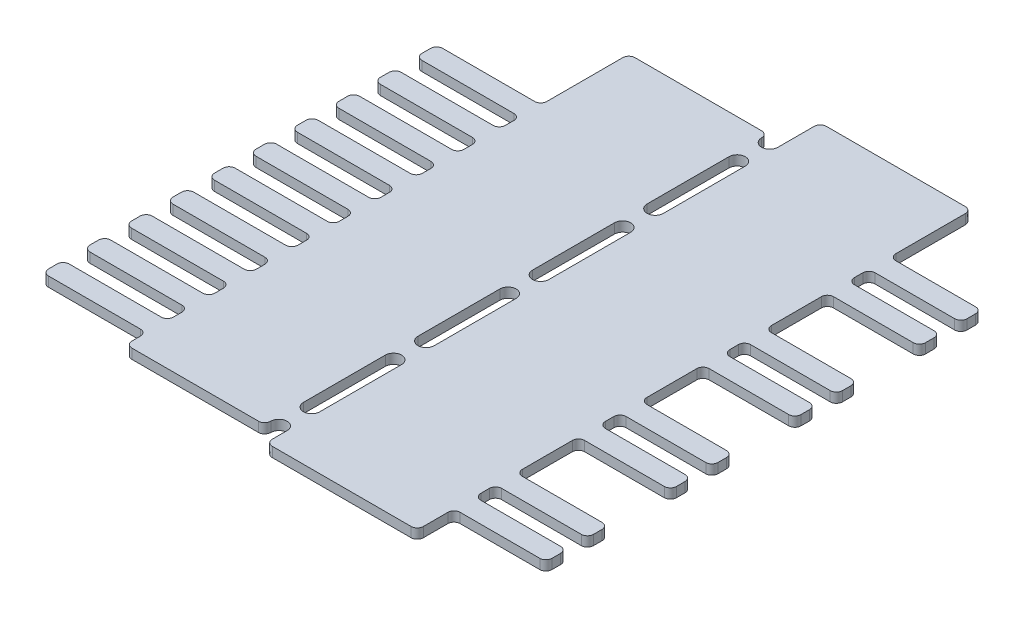
SolidWorks part; units mm, degrees
ref_plane "Front Plane" through (0, 0, 0) normal (0, 0, 1) x (1, 0, 0)
ref_plane "Top Plane" through (0, 0, 0) normal (0, 1, 0) x (1, 0, 0)
ref_plane "Right Plane" through (0, 0, 0) normal (1, 0, 0) x (0, 0, -1)
sketch "Sketch1" plane through (0, 0, 0) normal (0, 1, 0) x (1, 0, 0)
  line L0 (-0.75, 10) -> (-10.5, 10)
  line L2 (0, 9.25) -> (0, 0.75)
  line L5 (-11.25, 11.27) -> (0, 11.27) construction
  line L7 (-11.25, 10.75) -> (-11.25, 11.79)
  line L8 (-10.5, 12.54) -> (-0.75, 12.54)
  line L12 (0, 14.33) -> (0, 13.29)
  line L17 (-0.75, 15.08) -> (-10.5, 15.08)
  line L22 (-11.25, 15.83) -> (-11.25, 16.87)
  line L27 (-10.5, 17.62) -> (-0.75, 17.62)
  line L56 (17.75, 0) -> (0.75, 0)
  line L84 (0, 19.41) -> (0, 10.91) [skipped]
  line L85 (-0.75, 20.16) -> (-10.5, 20.16) [skipped]
  line L86 (-11.25, 20.91) -> (-11.25, 21.95) [skipped]
  line L87 (-10.5, 22.7) -> (-0.75, 22.7) [skipped]
  line L88 (0, 24.49) -> (0, 15.99) [skipped]
  line L89 (-0.75, 25.24) -> (-10.5, 25.24) [skipped]
  line L90 (-11.25, 25.99) -> (-11.25, 27.03) [skipped]
  line L91 (-10.5, 27.78) -> (-0.75, 27.78) [skipped]
  line L92 (0, 29.57) -> (0, 21.07) [skipped]
  line L93 (-0.75, 30.32) -> (-10.5, 30.32) [skipped]
  line L94 (-11.25, 31.07) -> (-11.25, 32.11) [skipped]
  line L95 (-10.5, 32.86) -> (-0.75, 32.86) [skipped]
  line L96 (0, 34.65) -> (0, 26.15) [skipped]
  line L97 (-0.75, 35.4) -> (-10.5, 35.4) [skipped]
  line L98 (-11.25, 36.15) -> (-11.25, 37.19) [skipped]
  line L99 (-10.5, 37.94) -> (-0.75, 37.94) [skipped]
  line L100 (0, 39.73) -> (0, 31.23) [skipped]
  line L101 (-0.75, 40.48) -> (-10.5, 40.48) [skipped]
  line L102 (-11.25, 41.23) -> (-11.25, 42.27) [skipped]
  line L103 (-10.5, 43.02) -> (-0.75, 43.02) [skipped]
  line L104 (0, 44.81) -> (0, 36.31) [skipped]
  line L105 (-0.75, 45.56) -> (-10.5, 45.56) [skipped]
  line L106 (-11.25, 46.31) -> (-11.25, 47.35) [skipped]
  line L107 (-10.5, 48.1) -> (-0.75, 48.1) [skipped]
  line L108 (0, 49.89) -> (0, 41.39) [skipped]
  line L109 (-0.75, 50.64) -> (-10.5, 50.64) [skipped]
  line L110 (-11.25, 51.39) -> (-11.25, 52.43) [skipped]
  line L111 (-10.5, 53.18) -> (-0.75, 53.18) [skipped]
  line L112 (0, 54.97) -> (0, 46.47) [skipped]
  line L113 (-0.75, 55.72) -> (-10.5, 55.72) [skipped]
  line L114 (-11.25, 56.47) -> (-11.25, 57.51) [skipped]
  line L115 (-10.5, 58.26) -> (-0.75, 58.26) [skipped]
  line L116 (-0.75, 25.24) -> (-10.5, 25.24)
  line L117 (-11.25, 25.99) -> (-11.25, 27.03)
  line L118 (-10.5, 27.78) -> (-0.75, 27.78)
  line L119 (0, 29.57) -> (0, 28.53)
  line L120 (-0.75, 30.32) -> (-10.5, 30.32)
  line L121 (-11.25, 31.07) -> (-11.25, 32.11)
  line L122 (-10.5, 32.86) -> (-0.75, 32.86)
  line L123 (-0.75, 40.48) -> (-10.5, 40.48)
  line L124 (-11.25, 41.23) -> (-11.25, 42.27)
  line L125 (-10.5, 43.02) -> (-0.75, 43.02)
  line L126 (0, 44.81) -> (0, 43.77)
  line L127 (-0.75, 45.56) -> (-10.5, 45.56)
  line L128 (-11.25, 46.31) -> (-11.25, 47.35)
  line L129 (-10.5, 48.1) -> (-0.75, 48.1)
  line L130 (-0.75, 55.72) -> (-10.5, 55.72)
  line L131 (-11.25, 56.47) -> (-11.25, 57.51)
  line L132 (-10.5, 58.26) -> (-0.75, 58.26)
  line L133 (0, 60.05) -> (0, 59.01)
  line L134 (-0.75, 60.8) -> (-10.5, 60.8)
  line L135 (-11.25, 61.55) -> (-11.25, 62.59)
  line L136 (-10.5, 63.34) -> (-0.75, 63.34)
  line L137 (0, 24.49) -> (0, 18.37)
  line L138 (0, 33.61) -> (0, 39.73)
  line L139 (0, 48.85) -> (0, 54.97)
  line L140 (0, 64.09) -> (0, 67.09)
  line L141 (0.75, 67.84) -> (17.75, 67.84)
  line L145 (38.25, 15.2205) -> (49.5, 15.2205)
  line L157 (37.5, 14.4705) -> (37.5, 5.183)
  line L158 (36.75, 4.433) -> (21.25, 4.433)
  line L160 (21.25, 66.0205) -> (36.75, 66.0205)
  line L188 (19.5, 5.183) -> (19.5, 54.2098) construction
  line L190 (18.5, 0.75) -> (18.5, 5.183)
  line L191 (20.5, 5.183) -> (19.5, 5.183) construction
  line L192 (20.5, 65.2705) -> (19.5, 65.2705) construction
  line L193 (20, 54.7098) -> (20, 58.84) construction
  line L194 (19, 58.84) -> (19, 54.7098) construction
  line L195 (18.5, 65.2705) -> (18.5, 67.09)
  line L196 (19.5, 54.2098) -> (19.5, 55.2098) construction
  line L197 (19.5, 55.2098) -> (19.5, 58.34) construction
  line L198 (19.5, 58.34) -> (19.5, 59.34) construction
  line L199 (19.5, 59.34) -> (19.5, 65.2705) construction
  line L200 (50.25, 15.9705) -> (50.25, 17.0105)
  line L201 (49.5, 17.7605) -> (38.25, 17.7605)
  line L202 (37.5, 18.5105) -> (37.5, 19.5505)
  line L204 (50.25, 21.0505) -> (50.25, 22.0905)
  line L205 (49.5, 22.8405) -> (38.25, 22.8405)
  line L206 (37.5, 23.5905) -> (37.5, 24.6305)
  line L207 (38.25, 20.3005) -> (49.5, 20.3005)
  line L208 (50.25, 26.1305) -> (50.25, 27.1705)
  line L209 (49.5, 27.9205) -> (38.25, 27.9205)
  line L210 (37.5, 28.6705) -> (37.5, 29.7105)
  line L212 (19.5, 65.2705) -> (18.5, 65.2705) construction
  line L213 (19.5, 65.2705) -> (19.5, 59.9038) construction
  line L214 (38.25, 25.3805) -> (49.5, 25.3805)
  line L215 (50.25, 31.2105) -> (50.25, 32.2505)
  line L216 (49.5, 33.0005) -> (38.25, 33.0005)
  line L217 (37.5, 33.7505) -> (37.5, 34.7905)
  line L218 (19.5, 5.183) -> (18.5, 5.183) construction
  line L219 (38.25, 30.4605) -> (49.5, 30.4605)
  line L220 (50.25, 36.2905) -> (50.25, 37.3305)
  line L221 (49.5, 38.0805) -> (38.25, 38.0805)
  line L222 (37.5, 38.8305) -> (37.5, 39.8705)
  line L223 (38.25, 35.5405) -> (49.5, 35.5405)
  line L224 (50.25, 41.3705) -> (50.25, 42.4105)
  line L225 (49.5, 43.1605) -> (38.25, 43.1605)
  line L226 (37.5, 43.9105) -> (37.5, 44.9505)
  line L227 (38.25, 40.6205) -> (49.5, 40.6205)
  line L228 (50.25, 46.4505) -> (50.25, 47.4905)
  line L229 (49.5, 48.2405) -> (38.25, 48.2405)
  line L230 (37.5, 48.9905) -> (37.5, 50.0305)
  line L231 (38.25, 45.7005) -> (49.5, 45.7005)
  line L232 (50.25, 51.5305) -> (50.25, 52.5705)
  line L233 (49.5, 53.3205) -> (38.25, 53.3205)
  line L234 (37.5, 54.0705) -> (37.5, 55.1105)
  line L235 (38.25, 50.7805) -> (49.5, 50.7805)
  line L236 (50.25, 56.6105) -> (50.25, 57.6505)
  line L237 (49.5, 58.4005) -> (38.25, 58.4005)
  line L238 (37.5, 59.1505) -> (37.5, 60.1905)
  line L239 (38.25, 55.8605) -> (49.5, 55.8605)
  line L240 (50.25, 61.6905) -> (50.25, 62.7305)
  line L241 (49.5, 63.4805) -> (38.25, 63.4805)
  line L242 (37.5, 64.2305) -> (37.5, 65.2705)
  line L243 (38.25, 60.9405) -> (49.5, 60.9405)
  arc A0 (-0.75, 12.54) -> (0, 13.29) centre (-0.75, 13.29) ccw
  arc A1 (-11.25, 11.79) -> (-10.5, 12.54) centre (-10.5, 11.79) cw
  arc A2 (-10.5, 10) -> (-11.25, 10.75) centre (-10.5, 10.75) cw
  arc A3 (0, 0.75) -> (0.75, 0) centre (0.75, 0.75) ccw
  arc A4 (-0.75, 10) -> (0, 9.25) centre (-0.75, 9.25) cw
  arc A5 (18.5, 0.75) -> (17.75, 0) centre (17.75, 0.75) cw
  arc A6 (-0.75, 15.08) -> (0, 14.33) centre (-0.75, 14.33) cw
  arc A7 (-10.5, 15.08) -> (-11.25, 15.83) centre (-10.5, 15.83) cw
  arc A8 (-11.25, 16.87) -> (-10.5, 17.62) centre (-10.5, 16.87) cw
  arc A9 (-0.75, 17.62) -> (0, 18.37) centre (-0.75, 18.37) ccw
  arc A44 (-0.75, 20.16) -> (0, 19.41) centre (-0.75, 19.41) cw [skipped]
  arc A45 (-10.5, 20.16) -> (-11.25, 20.91) centre (-10.5, 20.91) cw [skipped]
  arc A46 (-11.25, 21.95) -> (-10.5, 22.7) centre (-10.5, 21.95) cw [skipped]
  arc A47 (-0.75, 22.7) -> (0, 23.45) centre (-0.75, 23.45) ccw [skipped]
  arc A48 (-0.75, 25.24) -> (0, 24.49) centre (-0.75, 24.49) cw [skipped]
  arc A49 (-10.5, 25.24) -> (-11.25, 25.99) centre (-10.5, 25.99) cw [skipped]
  arc A50 (-11.25, 27.03) -> (-10.5, 27.78) centre (-10.5, 27.03) cw [skipped]
  arc A51 (-0.75, 27.78) -> (0, 28.53) centre (-0.75, 28.53) ccw [skipped]
  arc A52 (-0.75, 30.32) -> (0, 29.57) centre (-0.75, 29.57) cw [skipped]
  arc A53 (-10.5, 30.32) -> (-11.25, 31.07) centre (-10.5, 31.07) cw [skipped]
  arc A54 (-11.25, 32.11) -> (-10.5, 32.86) centre (-10.5, 32.11) cw [skipped]
  arc A55 (-0.75, 32.86) -> (0, 33.61) centre (-0.75, 33.61) ccw [skipped]
  arc A56 (-0.75, 35.4) -> (0, 34.65) centre (-0.75, 34.65) cw [skipped]
  arc A57 (-10.5, 35.4) -> (-11.25, 36.15) centre (-10.5, 36.15) cw [skipped]
  arc A58 (-11.25, 37.19) -> (-10.5, 37.94) centre (-10.5, 37.19) cw [skipped]
  arc A59 (-0.75, 37.94) -> (0, 38.69) centre (-0.75, 38.69) ccw [skipped]
  arc A60 (-0.75, 40.48) -> (0, 39.73) centre (-0.75, 39.73) cw [skipped]
  arc A61 (-10.5, 40.48) -> (-11.25, 41.23) centre (-10.5, 41.23) cw [skipped]
  arc A62 (-11.25, 42.27) -> (-10.5, 43.02) centre (-10.5, 42.27) cw [skipped]
  arc A63 (-0.75, 43.02) -> (0, 43.77) centre (-0.75, 43.77) ccw [skipped]
  arc A64 (-0.75, 45.56) -> (0, 44.81) centre (-0.75, 44.81) cw [skipped]
  arc A65 (-10.5, 45.56) -> (-11.25, 46.31) centre (-10.5, 46.31) cw [skipped]
  arc A66 (-11.25, 47.35) -> (-10.5, 48.1) centre (-10.5, 47.35) cw [skipped]
  arc A67 (-0.75, 48.1) -> (0, 48.85) centre (-0.75, 48.85) ccw [skipped]
  arc A68 (-0.75, 50.64) -> (0, 49.89) centre (-0.75, 49.89) cw [skipped]
  arc A69 (-10.5, 50.64) -> (-11.25, 51.39) centre (-10.5, 51.39) cw [skipped]
  arc A70 (-11.25, 52.43) -> (-10.5, 53.18) centre (-10.5, 52.43) cw [skipped]
  arc A71 (-0.75, 53.18) -> (0, 53.93) centre (-0.75, 53.93) ccw [skipped]
  arc A72 (-0.75, 55.72) -> (0, 54.97) centre (-0.75, 54.97) cw [skipped]
  arc A73 (-10.5, 55.72) -> (-11.25, 56.47) centre (-10.5, 56.47) cw [skipped]
  arc A74 (-11.25, 57.51) -> (-10.5, 58.26) centre (-10.5, 57.51) cw [skipped]
  arc A75 (-0.75, 58.26) -> (0, 59.01) centre (-0.75, 59.01) ccw [skipped]
  arc A76 (-0.75, 27.78) -> (0, 28.53) centre (-0.75, 28.53) ccw
  arc A77 (-11.25, 27.03) -> (-10.5, 27.78) centre (-10.5, 27.03) cw
  arc A78 (-10.5, 25.24) -> (-11.25, 25.99) centre (-10.5, 25.99) cw
  arc A79 (-0.75, 25.24) -> (0, 24.49) centre (-0.75, 24.49) cw
  arc A80 (-0.75, 30.32) -> (0, 29.57) centre (-0.75, 29.57) cw
  arc A81 (-10.5, 30.32) -> (-11.25, 31.07) centre (-10.5, 31.07) cw
  arc A82 (-11.25, 32.11) -> (-10.5, 32.86) centre (-10.5, 32.11) cw
  arc A83 (-0.75, 32.86) -> (0, 33.61) centre (-0.75, 33.61) ccw
  arc A84 (-0.75, 43.02) -> (0, 43.77) centre (-0.75, 43.77) ccw
  arc A85 (-11.25, 42.27) -> (-10.5, 43.02) centre (-10.5, 42.27) cw
  arc A86 (-10.5, 40.48) -> (-11.25, 41.23) centre (-10.5, 41.23) cw
  arc A87 (-0.75, 40.48) -> (0, 39.73) centre (-0.75, 39.73) cw
  arc A88 (-0.75, 45.56) -> (0, 44.81) centre (-0.75, 44.81) cw
  arc A89 (-10.5, 45.56) -> (-11.25, 46.31) centre (-10.5, 46.31) cw
  arc A90 (-11.25, 47.35) -> (-10.5, 48.1) centre (-10.5, 47.35) cw
  arc A91 (-0.75, 48.1) -> (0, 48.85) centre (-0.75, 48.85) ccw
  arc A92 (-0.75, 58.26) -> (0, 59.01) centre (-0.75, 59.01) ccw
  arc A93 (-11.25, 57.51) -> (-10.5, 58.26) centre (-10.5, 57.51) cw
  arc A94 (-10.5, 55.72) -> (-11.25, 56.47) centre (-10.5, 56.47) cw
  arc A95 (-0.75, 55.72) -> (0, 54.97) centre (-0.75, 54.97) cw
  arc A96 (-0.75, 60.8) -> (0, 60.05) centre (-0.75, 60.05) cw
  arc A97 (-10.5, 60.8) -> (-11.25, 61.55) centre (-10.5, 61.55) cw
  arc A98 (-11.25, 62.59) -> (-10.5, 63.34) centre (-10.5, 62.59) cw
  arc A99 (-0.75, 63.34) -> (0, 64.09) centre (-0.75, 64.09) ccw
  arc A100 (0, 67.09) -> (0.75, 67.84) centre (0.75, 67.09) cw
  arc A101 (17.75, 67.84) -> (18.5, 67.09) centre (17.75, 67.09) cw
  arc A107 (20.5, 65.2705) -> (21.25, 66.0205) centre (21.25, 65.2705) cw
  arc A144 (37.5, 5.183) -> (36.75, 4.433) centre (36.75, 5.183) cw
  arc A145 (21.25, 4.433) -> (20.5, 5.183) centre (21.25, 5.183) cw
  arc A147 (20.5, 5.183) -> (18.5, 5.183) centre (19.5, 5.183) ccw
  arc A148 (18.5, 5.183) -> (20.5, 5.183) centre (19.5, 5.183) ccw construction
  arc A149 (20, 58.84) -> (19, 58.84) centre (19.5, 58.84) ccw construction
  arc A150 (19, 54.7098) -> (20, 54.7098) centre (19.5, 54.7098) ccw construction
  arc A151 (19.5, 55.2098) -> (19, 54.7098) centre (19.5, 54.7098) ccw construction
  arc A152 (20, 54.7098) -> (19.5, 55.2098) centre (19.5, 54.7098) ccw construction
  arc A153 (19.5, 58.34) -> (20, 58.84) centre (19.5, 58.84) ccw construction
  arc A154 (19, 58.84) -> (19.5, 58.34) centre (19.5, 58.84) ccw construction
  arc A155 (18.5, 65.2705) -> (20.5, 65.2705) centre (19.5, 65.2705) ccw
  arc A156 (20.5, 65.2705) -> (18.5, 65.2705) centre (19.5, 65.2705) ccw construction
  arc A157 (38.25, 17.7605) -> (37.5, 18.5105) centre (38.25, 18.5105) cw
  arc A158 (50.25, 17.0105) -> (49.5, 17.7605) centre (49.5, 17.0105) ccw
  arc A159 (49.5, 15.2205) -> (50.25, 15.9705) centre (49.5, 15.9705) ccw
  arc A160 (37.5, 14.4705) -> (38.25, 15.2205) centre (38.25, 14.4705) cw
  arc A161 (38.25, 22.8405) -> (37.5, 23.5905) centre (38.25, 23.5905) cw
  arc A162 (50.25, 22.0905) -> (49.5, 22.8405) centre (49.5, 22.0905) ccw
  arc A163 (49.5, 20.3005) -> (50.25, 21.0505) centre (49.5, 21.0505) ccw
  arc A164 (37.5, 19.5505) -> (38.25, 20.3005) centre (38.25, 19.5505) cw
  arc A165 (38.25, 27.9205) -> (37.5, 28.6705) centre (38.25, 28.6705) cw
  arc A166 (50.25, 27.1705) -> (49.5, 27.9205) centre (49.5, 27.1705) ccw
  arc A167 (49.5, 25.3805) -> (50.25, 26.1305) centre (49.5, 26.1305) ccw
  arc A168 (37.5, 24.6305) -> (38.25, 25.3805) centre (38.25, 24.6305) cw
  arc A169 (38.25, 33.0005) -> (37.5, 33.7505) centre (38.25, 33.7505) cw
  arc A170 (50.25, 32.2505) -> (49.5, 33.0005) centre (49.5, 32.2505) ccw
  arc A171 (49.5, 30.4605) -> (50.25, 31.2105) centre (49.5, 31.2105) ccw
  arc A172 (37.5, 29.7105) -> (38.25, 30.4605) centre (38.25, 29.7105) cw
  arc A173 (38.25, 38.0805) -> (37.5, 38.8305) centre (38.25, 38.8305) cw
  arc A174 (50.25, 37.3305) -> (49.5, 38.0805) centre (49.5, 37.3305) ccw
  arc A175 (49.5, 35.5405) -> (50.25, 36.2905) centre (49.5, 36.2905) ccw
  arc A176 (37.5, 34.7905) -> (38.25, 35.5405) centre (38.25, 34.7905) cw
  arc A177 (38.25, 43.1605) -> (37.5, 43.9105) centre (38.25, 43.9105) cw
  arc A178 (50.25, 42.4105) -> (49.5, 43.1605) centre (49.5, 42.4105) ccw
  arc A179 (49.5, 40.6205) -> (50.25, 41.3705) centre (49.5, 41.3705) ccw
  arc A180 (37.5, 39.8705) -> (38.25, 40.6205) centre (38.25, 39.8705) cw
  arc A181 (38.25, 48.2405) -> (37.5, 48.9905) centre (38.25, 48.9905) cw
  arc A182 (50.25, 47.4905) -> (49.5, 48.2405) centre (49.5, 47.4905) ccw
  arc A183 (49.5, 45.7005) -> (50.25, 46.4505) centre (49.5, 46.4505) ccw
  arc A184 (37.5, 44.9505) -> (38.25, 45.7005) centre (38.25, 44.9505) cw
  arc A185 (38.25, 53.3205) -> (37.5, 54.0705) centre (38.25, 54.0705) cw
  arc A186 (50.25, 52.5705) -> (49.5, 53.3205) centre (49.5, 52.5705) ccw
  arc A187 (49.5, 50.7805) -> (50.25, 51.5305) centre (49.5, 51.5305) ccw
  arc A188 (37.5, 50.0305) -> (38.25, 50.7805) centre (38.25, 50.0305) cw
  arc A189 (38.25, 58.4005) -> (37.5, 59.1505) centre (38.25, 59.1505) cw
  arc A190 (50.25, 57.6505) -> (49.5, 58.4005) centre (49.5, 57.6505) ccw
  arc A191 (49.5, 55.8605) -> (50.25, 56.6105) centre (49.5, 56.6105) ccw
  arc A192 (37.5, 55.1105) -> (38.25, 55.8605) centre (38.25, 55.1105) cw
  arc A193 (38.25, 63.4805) -> (37.5, 64.2305) centre (38.25, 64.2305) cw
  arc A194 (50.25, 62.7305) -> (49.5, 63.4805) centre (49.5, 62.7305) ccw
  arc A195 (49.5, 60.9405) -> (50.25, 61.6905) centre (49.5, 61.6905) ccw
  arc A196 (37.5, 60.1905) -> (38.25, 60.9405) centre (38.25, 60.1905) cw
  arc A197 (37.5, 65.2705) -> (36.75, 66.0205) centre (36.75, 65.2705) ccw
  point P0 (0, 0)
  point P48 (-11.25, 12.54)
  point P69 (-11.25, 10)
  point P78 (0, 0)
  point P81 (0, 10)
  point P132 (29, 4.433)
  point P390 (43.875, 15.2205)
  dimension "D6" = 0.75
  dimension "D7" = 0.75
  dimension "D8" = 4
  dimension "D9" = 10.16
  dimension "D11" = 0.75
  dimension "D13" = 4.433
  dimension "D14" = 0.75
  dimension "D15" = 9
  dimension "D16" = 0.75
  dimension "D12" = 4.5
  dimension "D21" = 0.75
  dimension "D22" = 18.5
  dimension "D5" = 2
  dimension "D24" = 4.1302
  dimension "D25" = 17
  dimension "D17" = 0.75
  dimension "D1" = 2.54
  dimension "D2" = 10.5
  dimension "D3" = 10
  dimension "D4" = 10
  dimension "D10" = 5.08
  dimension "D18" = 10
  dimension "D19" = 12
  dimension "D20" = 2.54
  dimension "D23" = 5.08
  dimension "D26" = 10.7875
  dimension "D27" = 67.84
  dimension "D28" = 1.8195
  dimension "D29" = 1.8195
extrude "Boss-Extrude1" add sketch "Sketch1" along normal blind 1.2
sketch "Sketch2" plane through (0, 0, 0) normal (0, -1, 0) x (1, 0, 0)
  line L0 (19.5, -5.183) -> (19.5, -65.2705) construction
  line L1 (19.5, -61.2705) -> (19.5, -51.2505) construction
  line L2 (18.5, -61.2705) -> (18.5, -51.2505)
  line L3 (20.5, -61.2705) -> (20.5, -51.2505)
  line L4 (19.5, -35.2268) -> (0, -35.2268) construction
  line L5 (0, -39.73) -> (0, -33.61) construction
  line L6 (19.5, -47.2505) -> (19.5, -37.2305) construction
  line L7 (18.5, -47.2505) -> (18.5, -37.2305)
  line L8 (20.5, -47.2505) -> (20.5, -37.2305)
  line L9 (19.5, -23.203) -> (19.5, -33.223) construction
  line L10 (18.5, -23.203) -> (18.5, -33.223)
  line L11 (20.5, -23.203) -> (20.5, -33.223)
  line L12 (19.5, -9.183) -> (19.5, -19.203) construction
  line L13 (18.5, -9.183) -> (18.5, -19.203)
  line L14 (20.5, -9.183) -> (20.5, -19.203)
  arc A0 (18.5, -61.2705) -> (20.5, -61.2705) centre (19.5, -61.2705) ccw
  arc A1 (20.5, -51.2505) -> (18.5, -51.2505) centre (19.5, -51.2505) ccw
  circle A2 centre (19.5, -65.2705) radius 1 construction
  arc A3 (20.5, -65.2705) -> (18.5, -65.2705) centre (19.5, -65.2705) ccw construction
  arc A4 (18.5, -47.2505) -> (20.5, -47.2505) centre (19.5, -47.2505) ccw
  arc A5 (20.5, -37.2305) -> (18.5, -37.2305) centre (19.5, -37.2305) ccw
  arc A6 (18.5, -23.203) -> (20.5, -23.203) centre (19.5, -23.203) cw
  arc A7 (20.5, -33.223) -> (18.5, -33.223) centre (19.5, -33.223) cw
  arc A8 (18.5, -9.183) -> (20.5, -9.183) centre (19.5, -9.183) cw
  arc A9 (20.5, -19.203) -> (18.5, -19.203) centre (19.5, -19.203) cw
  point P6 (19.5, -56.2605)
  point P23 (19.5, -42.2405)
  point P28 (19.5, -28.213)
  point P35 (19.5, -14.193)
  dimension "D4" = 4
  dimension "D1" = 10.02
  dimension "D2" = 4
  dimension "D3" = 2
extrude "Cut-Extrude1" cut sketch "Sketch2" against normal through all
move or copy body "Body-Move/Copy1" bodies to move or copy 102 copy no rotation origin (17.625, 0, -34.92) rotation axis (0, 1, 0) rotation angle 180
equation "\"T\"= 1"
